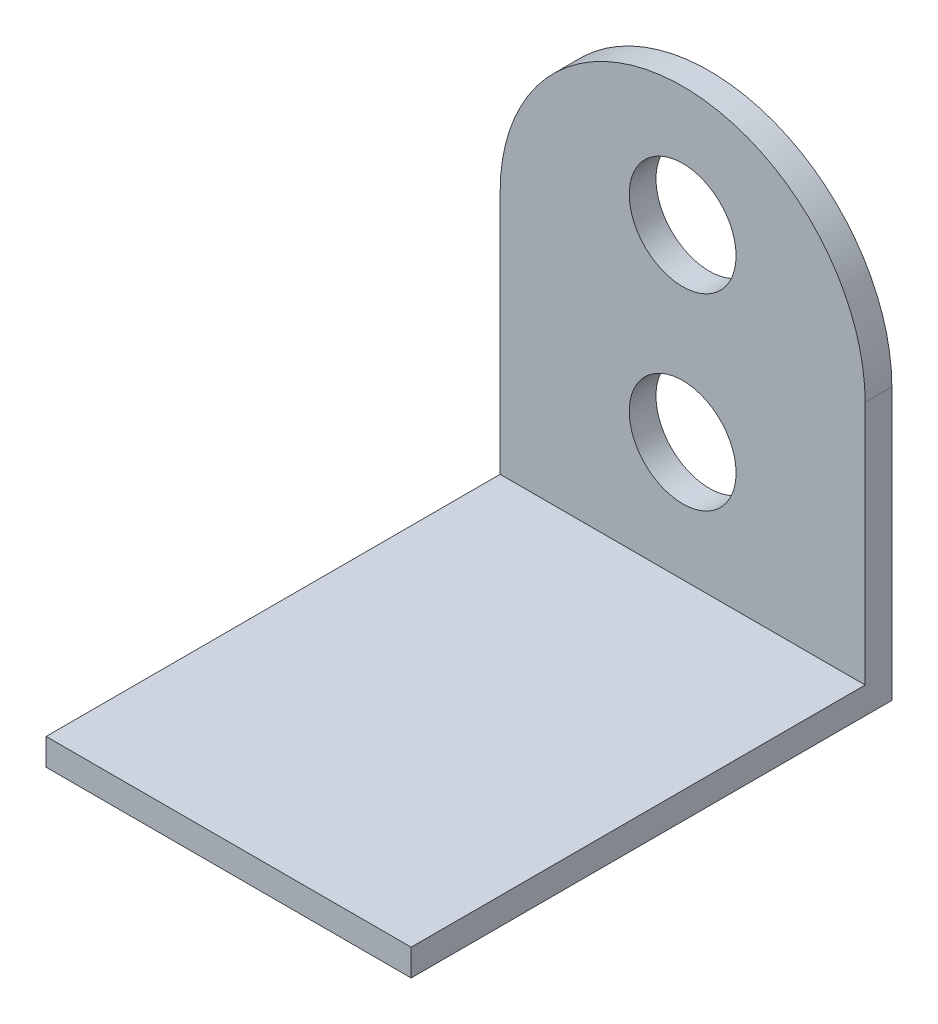
SolidWorks part; units mm, degrees
ref_plane "Front Plane" through (0, 0, 0) normal (0, 0, 1) x (1, 0, 0)
ref_plane "Top Plane" through (0, 0, 0) normal (0, 1, 0) x (1, 0, 0)
ref_plane "Right Plane" through (0, 0, 0) normal (1, 0, 0) x (0, 0, -1)
sketch "Sketch1" plane through (0, 0, 0) normal (0, 1, 0) x (1, 0, 0)
  line L1 (-124.7553, 19.9582) -> (-83.7553, 19.9582)
  line L2 (-124.7553, 19.9582) -> (-124.7553, -34.0418)
  line L3 (-124.7553, -34.0418) -> (-83.7553, -34.0418)
  line L4 (-83.7553, 19.9582) -> (-83.7553, -34.0418)
  line L5 (-124.7553, 19.9582) -> (-83.7553, -34.0418) construction
  line L6 (-124.7553, -34.0418) -> (-83.7553, 19.9582) construction
  point P0 (-104.2553, -7.0418)
extrude "Boss-Extrude1" add sketch "Sketch1" along normal blind 3
sketch "Sketch2" plane through (0, 3, 0) normal (0, 1, 0) x (1, 0, 0)
  line L0 (-83.7553, 19.9582) -> (-83.7553, 16.9582) construction
  line L1 (-83.7553, -34.0418) -> (-83.7553, 19.9582) construction
  line L3 (-83.7553, 16.9582) -> (-124.7553, 16.9582)
  line L4 (-83.7553, 16.9582) -> (-83.7553, 19.9582)
  line L5 (-83.7553, 19.9582) -> (-124.7553, 19.9582)
  line L6 (-124.7553, 16.9582) -> (-124.7553, 19.9582)
extrude "Boss-Extrude2" add sketch "Sketch2" along normal blind 48
sketch "Sketch4" plane through (0, 0, -16.9582) normal (0, 0, 1) x (1, 0, 0)
  line L0 (-104.2553, 3) -> (-104.2553, 37.5) construction
  line L1 (-124.7553, 3) -> (-83.7553, 3) construction
  circle A0 centre (-104.2553, 37.5) radius 6
extrude "Cut-Extrude1" cut sketch "Sketch4" against normal through all
sketch "Sketch5" plane through (0, 0, -16.9582) normal (0, 0, 1) x (1, 0, 0)
  line L0 (-104.2553, 3) -> (-104.2553, 30.5) construction
  line L1 (-124.7553, 3) -> (-83.7553, 3) construction
  line L3 (-124.7553, 30.5) -> (-83.7553, 30.5)
  line L4 (-124.7553, 30.5) -> (-124.7553, 51)
  line L5 (-124.7553, 51) -> (-83.7553, 51)
  line L6 (-83.7553, 30.5) -> (-83.7553, 51)
  circle A0 centre (-104.2553, 30.5) radius 20.5 construction
  arc A1 (-124.7553, 30.5) -> (-83.7553, 30.5) centre (-104.2553, 30.5) cw
extrude "Cut-Extrude3" cut sketch "Sketch5" against normal through all and the other way through all contours A1
sketch "Sketch12" plane through (0, 0, -16.9582) normal (0, 0, 1) x (1, 0, 0)
  line L0 (-104.2553, 37.5) -> (-104.2553, 5.8753) construction
  line L1 (-110.2553, 37.5) -> (-110.2553, 11.3085) construction
  circle A0 centre (-104.2553, 37.5) radius 6 construction
  circle A1 centre (-104.2553, 16.3788) radius 6
extrude "Cut-Extrude4" cut sketch "Sketch12" against normal through all
